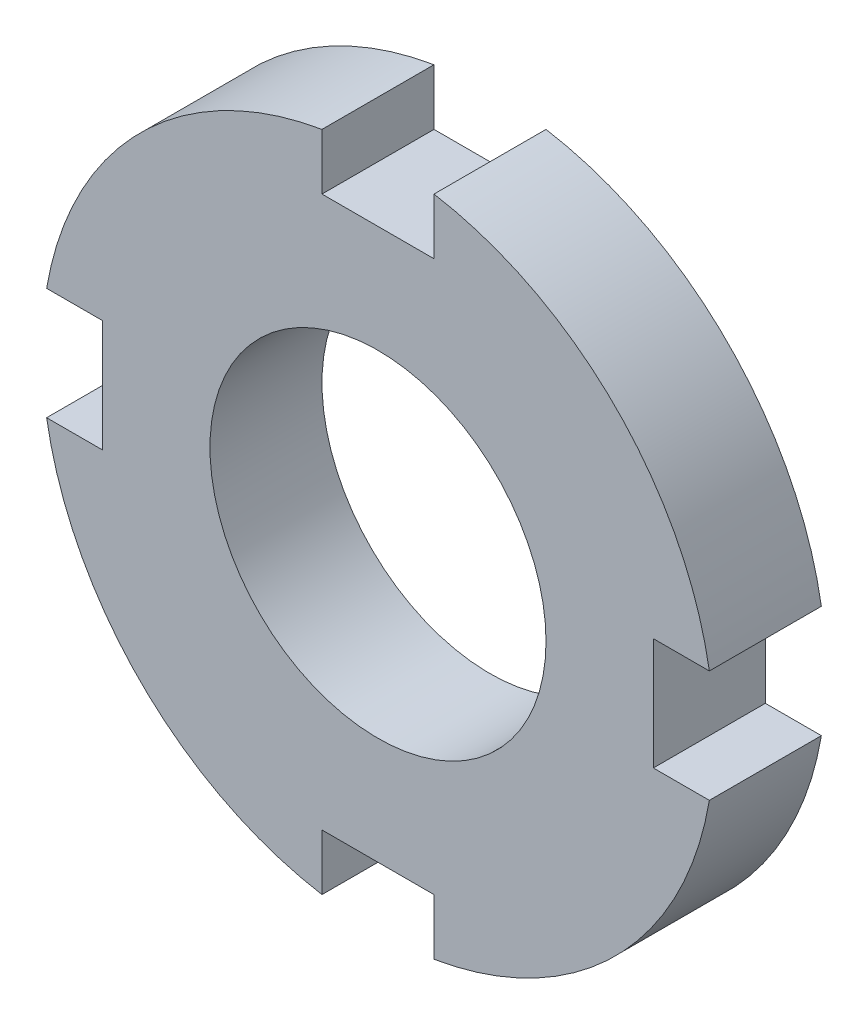
SolidWorks part; units mm, degrees
ref_plane "前视基准面" through (0, 0, 0) normal (0, 0, 1) x (1, 0, 0)
ref_plane "上视基准面" through (0, 0, 0) normal (0, 1, 0) x (1, 0, 0)
ref_plane "右视基准面" through (0, 0, 0) normal (1, 0, 0) x (0, 0, -1)
sketch "草图1" plane through (0, 0, 0) normal (0, 0, 1) x (1, 0, 0)
  line L0 (0, 0) -> (0, 16.2193) construction
  line L1 (9.8322, 2) -> (11.8322, 2)
  line L2 (9.8322, 2) -> (9.8322, -2)
  line L3 (9.8322, -2) -> (11.8322, -2)
  line L4 (2, -9.8322) -> (2, -11.8322)
  line L5 (-2, 9.8322) -> (2, 9.8322)
  line L6 (-2, 9.8322) -> (-2, 11.8322)
  line L7 (2, -9.8322) -> (-2, -9.8322)
  line L8 (-2, -9.8322) -> (-2, -11.8322)
  line L9 (2, 9.8322) -> (2, 11.8322)
  line L10 (-9.8322, -2) -> (-11.8322, -2)
  line L11 (-9.8322, -2) -> (-9.8322, 2)
  line L12 (-9.8322, 2) -> (-11.8322, 2)
  arc A0 (-2, 11.8322) -> (-11.8322, 2) centre (0, 0) ccw
  arc A1 (11.8322, 2) -> (2, 11.8322) centre (0, 0) ccw
  arc A2 (-11.8322, -2) -> (-2, -11.8322) centre (0, 0) ccw
  arc A3 (2, -11.8322) -> (11.8322, -2) centre (0, 0) ccw
  circle A4 centre (0, 0) radius 6
  point P4 (-2, 0)
  point P5 (-2, 16.2193)
  point P6 (2, 0)
  point P7 (2, 16.2193)
  point P9 (3.5123, 11.8322)
  point P13 (3.5123, 9.8322)
  dimension "D1" = 24
  dimension "D2" = 12
extrude "拉伸1" add sketch "草图1" along normal blind 4
